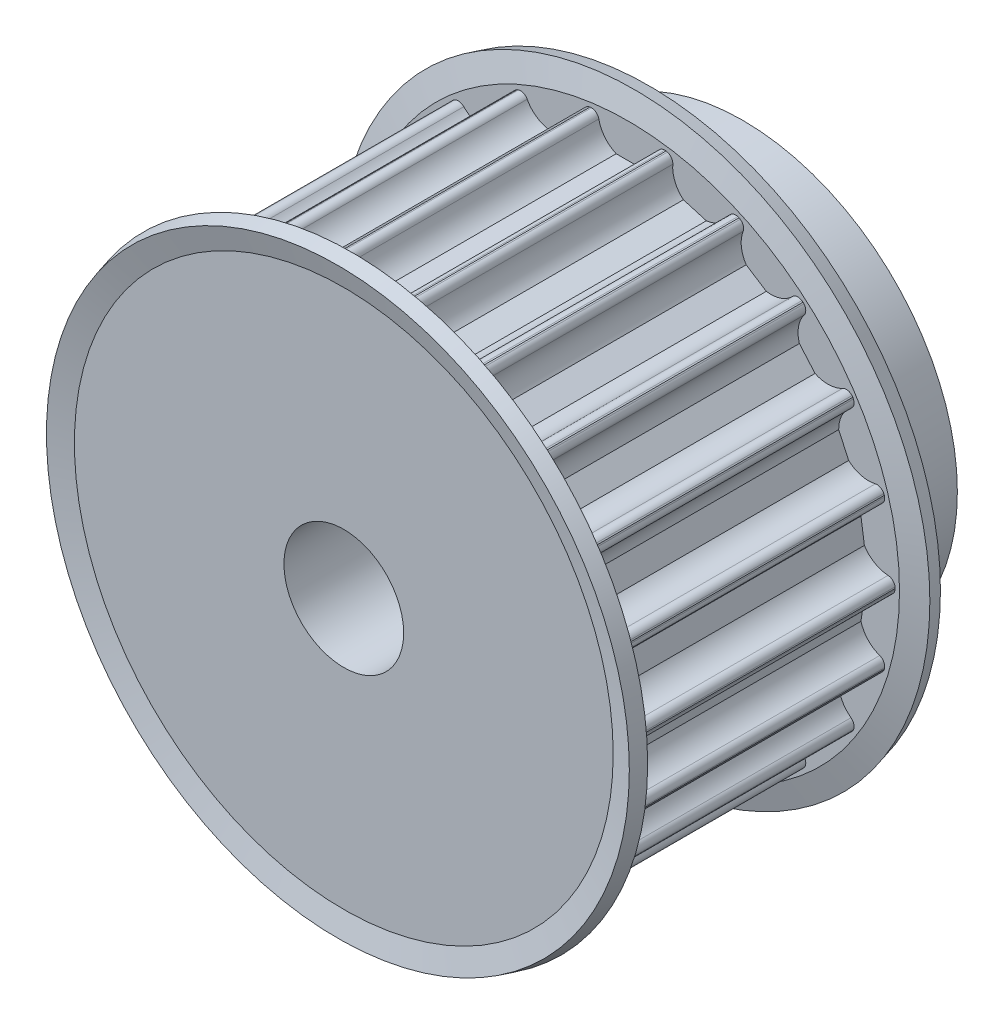
SolidWorks part; units mm, degrees
ref_plane "Front Plane" through (0, 0, 0) normal (0, 0, 1) x (1, 0, 0)
ref_plane "Top Plane" through (0, 0, 0) normal (0, 1, 0) x (1, 0, 0)
ref_plane "Right Plane" through (0, 0, 0) normal (1, 0, 0) x (0, 0, -1)
ref_axis "Axis1" through (0, 0, 55) along (0, 0, -1)
sketch "Sketch1" plane through (0, 0, 0) normal (1, 0, 0) x (0, 0, -1)
  line L0 (0, 6) -> (0, 27.25)
  line L1 (0, 27.25) -> (30, 27.25)
  line L2 (30, 27.25) -> (30, 21.5)
  line L3 (30, 21.5) -> (40, 21.5)
  line L4 (40, 21.5) -> (40, 6)
  line L5 (40, 6) -> (0, 6)
  dimension "D1" = 6
  dimension "D2" = 30
  dimension "D3" = 10
  dimension "D4" = 15.5
  dimension "D5" = 21.25
revolve "Revolve1" add sketch "Sketch1" angle 360 about axis through (0, 0, 55) along (0, 0, -1)
sketch "Sketch2" plane through (0, 0, 0) normal (0, 0, 1) x (1, 0, 0)
  line L0 (3.6742, 26.5) -> (4, 26.5)
  line L1 (-4, 28.5) -> (4, 28.5)
  line L2 (-4, 28.5) -> (-4, 26.5)
  line L3 (-4, 26.5) -> (-3.6742, 26.5)
  line L4 (4, 28.5) -> (4, 26.5)
  line L5 (-1.199, 23.75) -> (1.199, 23.75)
  arc A0 (-2.9394, 25.9) -> (-1.199, 23.75) centre (0, 26.5) ccw
  arc A1 (-2.9394, 25.9) -> (-3.6742, 26.5) centre (-3.6742, 25.75) ccw
  arc A2 (2.9394, 25.9) -> (3.6742, 26.5) centre (3.6742, 25.75) cw
  arc A3 (1.199, 23.75) -> (2.9394, 25.9) centre (0, 26.5) ccw
  point P11 (-3, 26.5)
  point P14 (3, 26.5)
  dimension "D1" = 3
  dimension "D5" = 0.75
  dimension "D6" = 0.75
  dimension "D2" = 2
  dimension "D3" = 8
  dimension "D4" = 26.5
  dimension "D7" = 2.75
extrude "Cut-Extrude1" cut sketch "Sketch2" against normal through all
pattern_circular "CirPattern1" count 22 over 360 about axis through (0, 0, 0) along (0, 0, 1) of "Cut-Extrude1"
sketch "Sketch3" plane through (0, 0, 0) normal (1, 0, 0) x (0, 0, -1)
  line L0 (0, 25.679) -> (0, 23.1257) construction
  line L1 (0, 22.2) -> (1.5, 22.2)
  line L2 (0, 22.2) -> (0, 27.2)
  line L3 (0, 27.2) -> (1.5, 27.2) construction
  line L4 (1.5, 22.2) -> (1.5, 27.2)
  line L5 (1.5, 27.2) -> (0.0511, 26.8118) construction
  line L6 (1.5, 27.2) -> (0.8569, 29.6)
  line L7 (0.0511, 26.8118) -> (-0.592, 29.2118)
  line L8 (0.8569, 29.6) -> (-0.592, 29.2118)
  line L9 (0, 26.5) -> (30, 26.5) construction
  line L10 (15, 26.4617) -> (15, -33.0182) construction
  line L11 (30, 26.4617) -> (0, 26.4617) construction
  line L12 (28.5, 27.2) -> (29.9489, 26.8118) construction
  line L13 (30, 27.2) -> (28.5, 27.2) construction
  line L14 (29.1431, 29.6) -> (30.592, 29.2118)
  line L15 (29.9489, 26.8118) -> (30.592, 29.2118)
  line L16 (28.5, 27.2) -> (29.1431, 29.6)
  line L17 (28.5, 22.2) -> (28.5, 27.2)
  line L18 (30, 22.2) -> (30, 27.2)
  line L19 (30, 22.2) -> (28.5, 22.2)
  point P15 (15, 27.2)
  point P16 (15, -33.0182)
  dimension "D1" = 1.5
  dimension "D2" = 5
  dimension "D3" = 1.5
  dimension "D4" = 2.4
  dimension "D5" = 165
  dimension "D6" = 0.7
revolve "Revolve2" add sketch "Sketch3" angle 360 about axis through (0, 0, 55) along (0, 0, -1)
